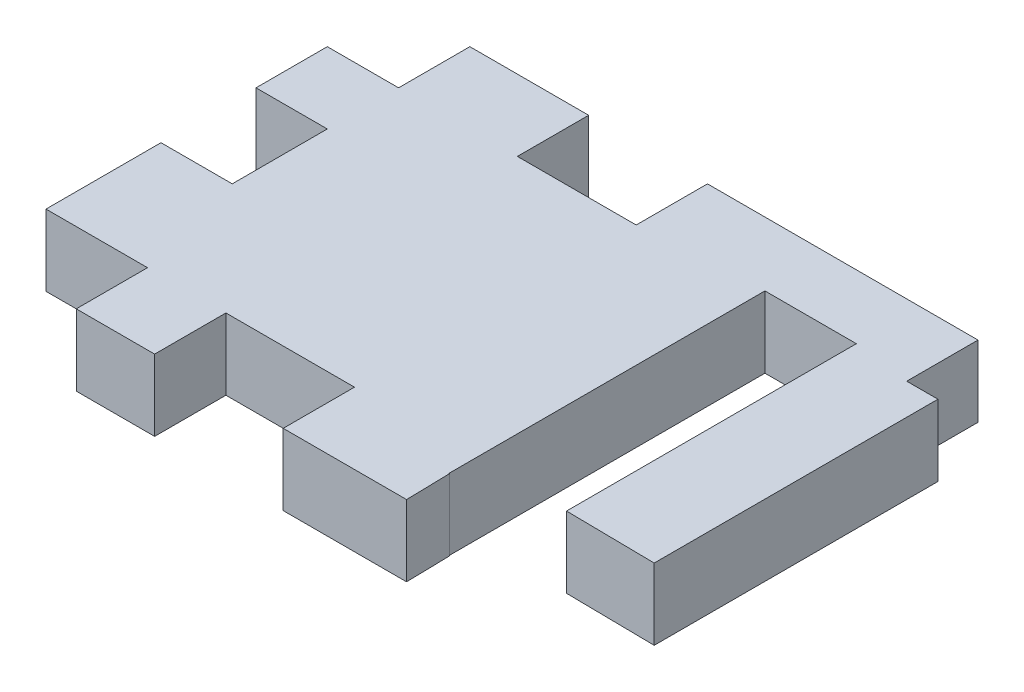
SolidWorks part; units mm, degrees
ref_plane "Front Plane" through (0, 0, 0) normal (0, 0, 1) x (1, 0, 0)
ref_plane "Top Plane" through (0, 0, 0) normal (0, 1, 0) x (1, 0, 0)
ref_plane "Right Plane" through (0, 0, 0) normal (1, 0, 0) x (0, 0, -1)
sketch "Sketch1" plane through (0, 0, 0) normal (0, 1, 0) x (1, 0, 0)
  line L1 (0, 0) -> (30, 0)
  line L2 (0, 0) -> (0, -30)
  line L3 (0, -30) -> (30, -30)
  line L4 (30, 0) -> (30, -30)
  dimension "D1" = 30
  dimension "D2" = 30
extrude "Boss-Extrude1" add sketch "Sketch1" along normal blind 3
sketch "Sketch2" plane through (0, 0, 0) normal (0, -1, 0) x (1, 0, 0)
  line L0 (30, 0) -> (0, 0) construction
  line L1 (8, 3) -> (13, 3)
  line L2 (8, 3) -> (8, 0)
  line L3 (8, 0) -> (13, 0)
  line L4 (13, 3) -> (13, 0)
  line L6 (24.3862, 3) -> (25.7, 3)
  line L7 (24.3862, 3) -> (24.3862, 0)
  line L8 (24.3862, 0) -> (25.7, 0)
  line L9 (25.7, 3) -> (25.7, 0)
  line L11 (3, 0) -> (0, 0)
  line L12 (3, 0) -> (3, 3)
  line L13 (3, 3) -> (0, 3)
  line L14 (0, 0) -> (0, 3)
  line L15 (0, 0) -> (0, 30) construction
  line L18 (3, 10) -> (0, 10)
  line L19 (3, 10) -> (3, 6)
  line L20 (3, 6) -> (0, 6)
  line L21 (0, 10) -> (0, 6)
  dimension "D1" = 4
  dimension "D2" = 3
extrude "Cut-Extrude1" cut sketch "Sketch2" against normal blind 3
sketch "Sketch3" plane through (0, 0, 0) normal (0, -1, 0) x (1, 0, 0)
  line L1 (21.9596, 2.6929) -> (18.1117, 2.6929)
  line L2 (21.9596, 2.6929) -> (21.9596, 15.9875)
  line L3 (21.9596, 15.9875) -> (18.1117, 15.9875)
  line L4 (18.1117, 2.6929) -> (18.1117, 15.9875)
extrude "Cut-Extrude2" cut sketch "Sketch3" against normal blind 3
sketch "Sketch4" plane through (0, 0, 0) normal (0, -1, 0) x (1, 0, 0)
  line L0 (0, 14.839) -> (25.9662, 14.839) construction
  line L1 (0, 10) -> (0, 30) construction
  line L2 (0, 17.839) -> (25.4273, 17.839) construction
  line L3 (0, 14.839) -> (4.2733, 14.839)
  line L4 (4.2733, 14.839) -> (4.2733, 17.839)
  line L5 (4.2733, 17.839) -> (7.572, 17.839)
  line L6 (7.572, 17.839) -> (7.572, 14.839)
  line L7 (7.572, 14.839) -> (12.9831, 14.839)
  line L8 (12.9831, 14.839) -> (12.9831, 17.839)
  line L9 (12.9831, 17.839) -> (18.1735, 17.839)
  line L10 (18.1735, 17.839) -> (18.1117, 14.839)
  line L11 (18.1117, 15.9875) -> (18.1117, 2.6929) construction
  line L12 (18.1117, 14.839) -> (30, 15)
  line L13 (30, 30) -> (30, 0) construction
  line L14 (30, 15) -> (30, 36.6422)
  line L15 (30, 36.6422) -> (-3.6626, 36.6422)
  line L16 (-3.6626, 36.6422) -> (-3.6626, 14.839)
  line L17 (-3.6626, 14.839) -> (0, 14.839)
  dimension "D1" = 3
extrude "Cut-Extrude3" cut sketch "Sketch4" against normal blind 3
sketch "Sketch6" plane through (0, 3, 0) normal (0, 1, 0) x (1, 0, 0)
  line L0 (25.7, 0) -> (25.7, -20.0652)
  line L1 (25.7, -20.0652) -> (34.53, -19.4896)
  line L2 (34.53, -19.4896) -> (33.1569, 1.5769)
  line L3 (33.1569, 1.5769) -> (28.6409, 2.8395)
  line L4 (28.6409, 2.8395) -> (25.7, 0)
extrude "Cut-Extrude4" cut sketch "Sketch6" against normal blind 10
